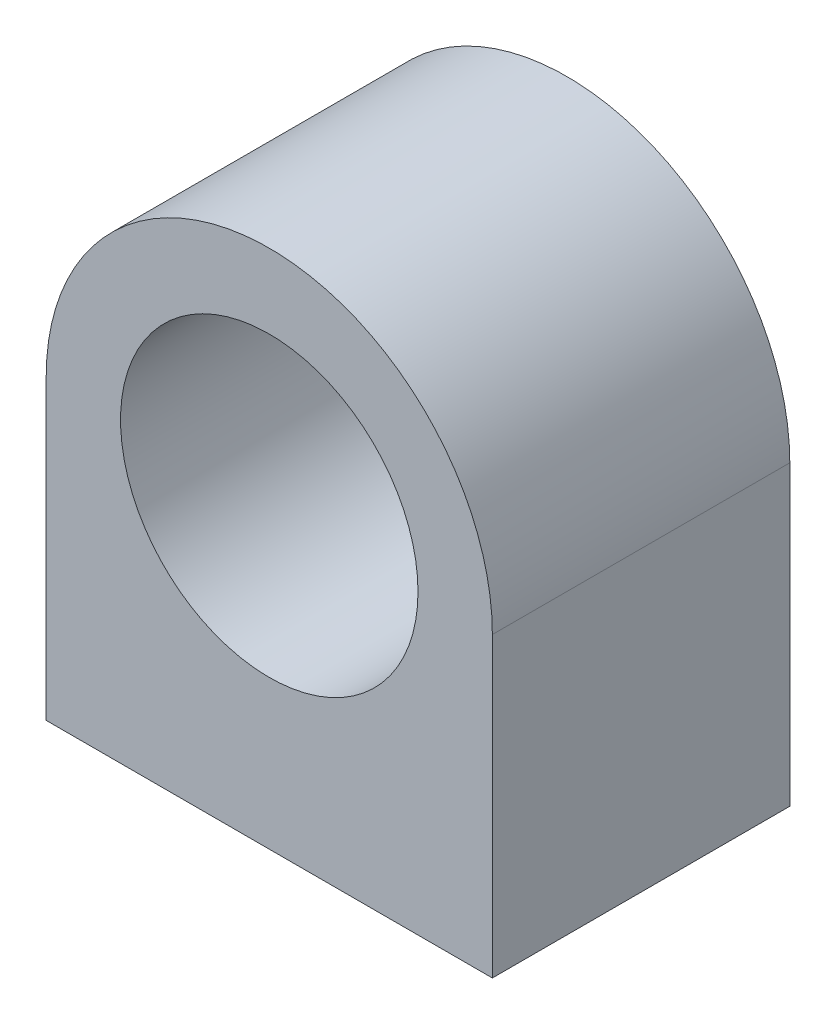
SolidWorks part; units mm, degrees
ref_plane "Front Plane" through (0, 0, 0) normal (0, 0, 1) x (1, 0, 0)
ref_plane "Top Plane" through (0, 0, 0) normal (0, 1, 0) x (1, 0, 0)
ref_plane "Right Plane" through (0, 0, 0) normal (1, 0, 0) x (0, 0, -1)
sketch "Sketch1" plane through (0, 0, 0) normal (0, 0, 1) x (1, 0, 0)
  line L0 (-19.05, 25.4) -> (-19.05, 0)
  line L1 (-19.05, 0) -> (19.05, 0)
  line L2 (19.05, 0) -> (19.05, 25.4)
  arc A0 (19.05, 25.4) -> (-19.05, 25.4) centre (0, 25.4) ccw
  circle A1 centre (0, 25.4) radius 12.7
  dimension "D1" = 38.1
  dimension "D3" = 25.4
  dimension "D2" = 25.4
extrude "Boss-Extrude1" add sketch "Sketch1" along normal mid plane 25.4
hole_wizard "Hole1" positions "Sketch2" profile "Sketch3" legacy
sketch "Sketch2" plane through (0, 0, 0) normal (0, -1, 0) x (-1, 0, 0)
  point P0 (-12.7, 0)
  point P2 (12.7, 0)
  dimension "D1" = 12.7
  dimension "D2" = 25.4
sketch "Sketch3" plane through (12.7, 0, 0) normal (1, 0, 0) x (0, 0, -1)
  line L0 (0, 0) -> (0, 12.7)
  line L1 (0, 12.7) -> (3.175, 12.7)
  line L2 (3.175, 12.7) -> (3.175, 0)
  line L3 (3.175, 0) -> (0, 0)
  line L4 (0, 110) -> (0, -10) construction
  dimension "Diameter" = 6.35
  dimension "Depth" = 12.7
